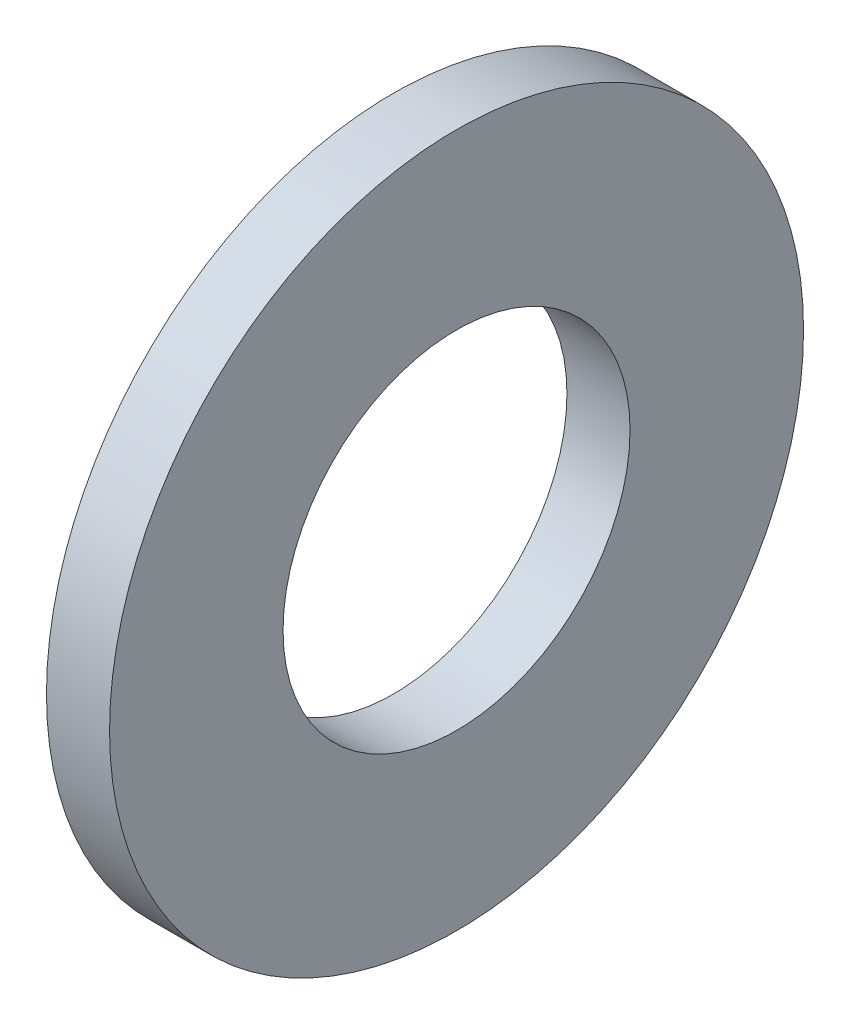
SolidWorks part; units mm, degrees
material "1.0406 (C25)"
ref_plane "Plane1" through (0, 0, 0) normal (0, 0, 1) x (1, 0, 0)
ref_plane "Plane2" through (0, 0, 0) normal (0, 1, 0) x (1, 0, 0)
ref_plane "Plane3" through (0, 0, 0) normal (1, 0, 0) x (0, 0, -1)
sketch "Sketch1" plane through (0, 0, 0) normal (1, 0, 0) x (0, 0, -1)
  circle A0 centre (0, 0) radius 2.75
  circle A1 centre (0, 0) radius 5.5
  dimension "Insid_dia" = 5.5
  dimension "OutsideDia" = 11
extrude "Base-Extrude" add sketch "Sketch1" along normal blind 1
